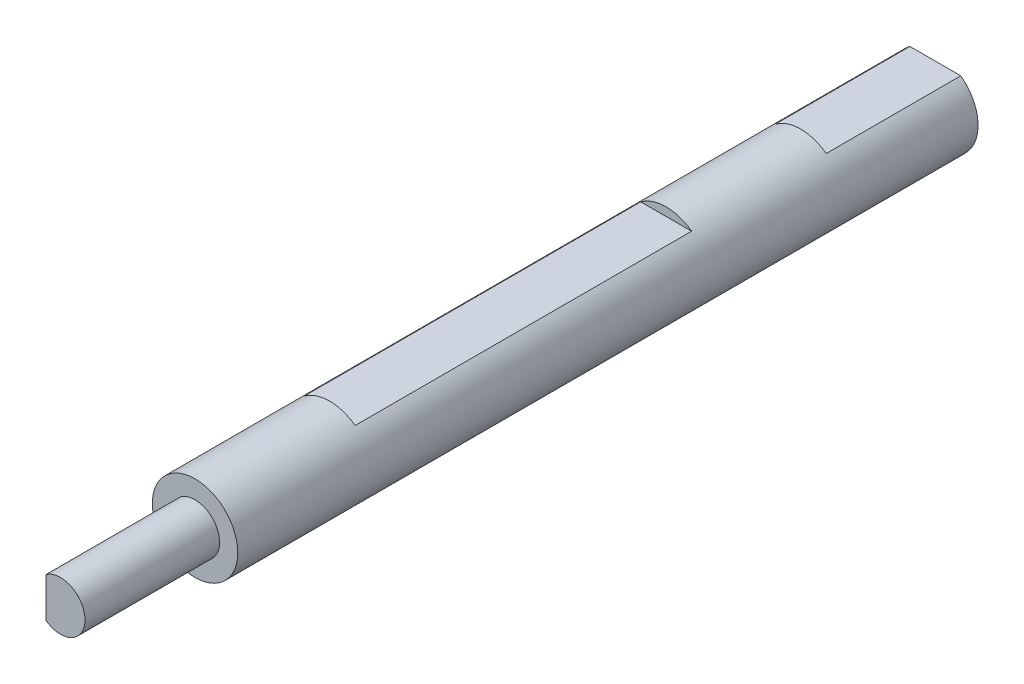
SolidWorks part; units mm, degrees
ref_plane "Front Plane" through (0, 0, 0) normal (0, 0, 1) x (1, 0, 0)
ref_plane "Top Plane" through (0, 0, 0) normal (0, 1, 0) x (1, 0, 0)
ref_plane "Right Plane" through (0, 0, 0) normal (1, 0, 0) x (0, 0, -1)
sketch "Sketch1" plane through (0, 0, 0) normal (0, 0, 1) x (1, 0, 0)
  circle A0 centre (0, 0) radius 3.175
  dimension "D1" = 6.35
extrude "Boss-Extrude1" add sketch "Sketch1" along normal blind 65
sketch "Sketch2" plane through (0, 0, 0) normal (0, 0, -1) x (-1, 0, 0)
  line L0 (-1.8916, 2.55) -> (1.8916, 2.55)
  line L1 (-1.8916, -2.55) -> (1.8916, -2.55)
  line L2 (0, 2.55) -> (0, -2.55) construction
  circle A0 centre (0, 0) radius 3.175 construction
  arc A1 (-1.8916, -2.55) -> (1.8916, -2.55) centre (0, 0) ccw
  arc A2 (1.8916, 2.55) -> (-1.8916, 2.55) centre (0, 0) ccw
  point P4 (0, 0)
  dimension "D1" = 5.1
extrude "Cut-Extrude1" cut sketch "Sketch2" against normal blind 10
ref_plane "Plane1" through (0, 0, 20) normal (0, 0, -1) x (-1, 0, 0)
sketch "Sketch3" plane through (0, 0, 20) normal (0, 0, -1) x (-1, 0, 0)
  line L0 (-1.8916, 2.55) -> (1.8916, 2.55)
  arc A0 (1.8916, 2.55) -> (-1.8916, 2.55) centre (0, 0) ccw
  arc A1 (1.8916, -2.55) -> (1.8916, 2.55) centre (0, 0) ccw construction
  point P9 (2.0843, 2.395)
extrude "Cut-Extrude2" cut sketch "Sketch3" against normal blind 25
sketch "Sketch4" plane through (0, 0, 65) normal (0, 0, 1) x (1, 0, 0)
  line L0 (-1.073, -1.4787) -> (-1.073, 1.4787)
  line L1 (1.827, -1.5137) -> (1.827, 1.8154) construction
  arc A0 (-1.073, -1.4787) -> (-1.073, 1.4787) centre (0, 0) ccw
  circle A1 centre (0, 0) radius 3.175
  circle A2 centre (0, 0) radius 3.175 construction
  dimension "D1" = 3.654
  dimension "D2" = 2.9
extrude "Cut-Extrude3" cut sketch "Sketch4" against normal blind 10
